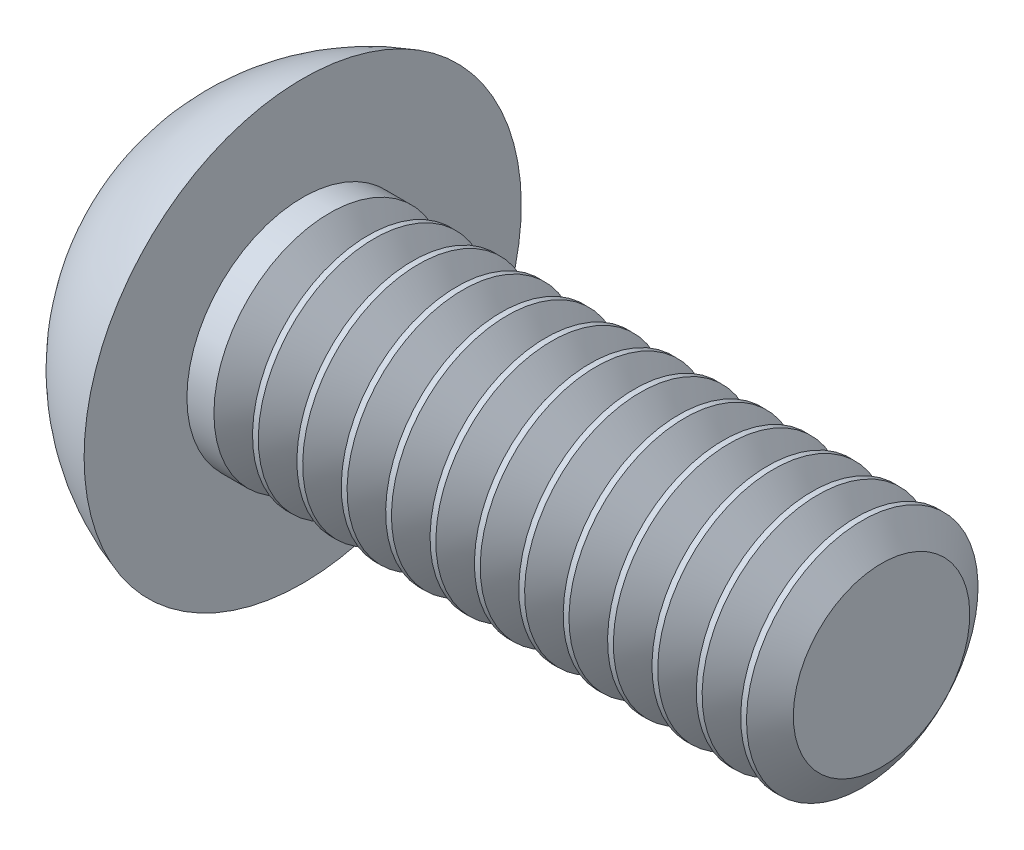
SolidWorks part; units mm, degrees
ref_plane "Plane1" through (0, 0, 0) normal (0, 0, 1) x (1, 0, 0)
ref_plane "Plane2" through (0, 0, 0) normal (0, 1, 0) x (1, 0, 0)
ref_plane "Plane3" through (0, 0, 0) normal (1, 0, 0) x (0, 0, -1)
sketch "BodySke" plane through (0, 0, 0) normal (0, 0, 1) x (1, 0, 0)
  line L0 (0, 0) -> (82.55, 0) construction
  line L1 (20.32, 0) -> (20.32, 3.175)
  line L2 (20.32, 3.175) -> (4.445, 3.175)
  line L3 (4.445, 3.175) -> (4.445, 5.9944)
  line L4 (20.32, -3.175) -> (4.445, -3.175) construction
  line L5 (4.445, -3.175) -> (4.445, -5.9944) construction
  line L6 (5.715, 12.7) -> (5.715, -3.175) construction
  line L7 (20.32, 0) -> (0, 0)
  line L8 (4.445, 12.7) -> (4.445, -3.175) construction
  arc A0 (0, 0) -> (4.445, 5.9944) centre (6.2644, 0) cw
  dimension "Head_ht" = 4.445
  dimension "Diameter" = 6.35
  dimension "Head_dia" = 11.9888
  dimension "Length" = 15.875
  dimension "Thread_nom" = 15.875
  dimension "Advance" = 1.27
revolve "Base-Revolve" add sketch "BodySke"
cosmetic thread "ThreadCosmetic" [suppressed]
revolve "ThreadSchematic" cut sketch "ThdSchSke" angle 360 about L3
sketch "ThdSchSke" plane through (0, 0, 0) normal (0, 0, 1) x (1, 0, 0)
  line L0 (5.715, -2.4193) -> (5.1859, -3.175)
  line L1 (5.715, -2.4193) -> (6.2441, -3.175)
  line L2 (6.2441, -3.175) -> (6.2441, -3.9688)
  line L3 (-3.175, 0) -> (5.1513, 0) construction
  line L5 (6.2441, -3.9688) -> (5.1859, -3.9688)
  line L6 (5.1859, -3.9688) -> (5.1859, -3.175)
  dimension "Diameter" = 6.35
  dimension "SideAngle" = 55
  dimension "VeeAngle" = 70
  dimension "Thread_minor" = 4.8387
  dimension "Overcut" = 7.9375
  dimension "Start" = 5.715
sketch "Sketch2" plane through (0, 0, 0) normal (1, 0, 0) x (0, 0, -1)
  line L0 (5.9944, 0.9525) -> (-5.9944, 0.9525)
  line L1 (5.9944, 0.9525) -> (5.9944, -0.9525)
  line L2 (-5.9944, -0.9525) -> (5.9944, -0.9525)
  line L3 (-5.9944, -0.9525) -> (-5.9944, 0.9525)
  dimension "D1" = 11.9888
  dimension "Slot_width" = 1.905
  dimension "D2" = 5.9944
  dimension "D3" = 0.9525
extrude "Slot" [suppressed] cut sketch "Sketch2" along normal blind 2.7686
sketch "Sketch3" plane through (0, 0, 0) normal (1, 0, 0) x (0, 0, -1)
  line L0 (0.6858, -3.8989) -> (-0.6858, -3.8989)
  line L1 (0.6858, -3.8989) -> (0.6858, 3.8989)
  line L2 (-0.6858, 3.8989) -> (0.6858, 3.8989)
  line L3 (-0.6858, 3.8989) -> (-0.6858, -3.8989)
  dimension "Cross_width" = 1.3716
  dimension "D1" = 0.6858
  dimension "Cross_dia" = 7.7978
  dimension "D2" = 3.8989
ref_plane "Plane4" through (4.5974, 0, 0) normal (1, 0, 0) x (0, 0, -1)
sketch "Sketch4" plane through (4.5974, 0, 0) normal (1, 0, 0) x (0, 0, -1)
  line L0 (0.3429, -0.3429) -> (-0.3429, -0.3429)
  line L1 (0.3429, -0.3429) -> (0.3429, 0.3429)
  line L2 (-0.3429, 0.3429) -> (0.3429, 0.3429)
  line L3 (-0.3429, 0.3429) -> (-0.3429, -0.3429)
  dimension "D1" = 0.6858
  dimension "D2" = 0.3429
  dimension "D3" = 0.6858
  dimension "D4" = 0.3429
loft "Cross" cut profiles "Sketch3", "Sketch4"
pattern_circular "CirPattern1" count 2 every 90 about axis through (0, 0, 0) along (1, 0, 0) of "Cross"
pattern_linear "ThdSchPat" count 13 spacing 1.2171 along (1, 0, 0) of "ThreadSchematic"
equation "\"D1@Sketch2\" = \"Head_dia@BodySke\""
equation "\"D2@Sketch2\" = \"D1@Sketch2\" / 2"
equation "\"D3@Sketch2\" = \"Slot_width@Sketch2\" / 2"
equation "\"D1@Sketch3\" = \"Cross_width@Sketch3\" / 2"
equation "\"D2@Sketch3\" = \"Cross_dia@Sketch3\" / 2"
equation "\"D1@Sketch4\" = \"Cross_width@Sketch3\" *.5"
equation "\"D2@Sketch4\" = \"D1@Sketch4\" / 2"
equation "\"D3@Sketch4\" = \"D1@Sketch4\""
equation "\"D4@Sketch4\" = \"D2@Sketch4\""
equation "\"Thread_length@ThreadCosmetic\" = ((sgn( (\"Length@BodySke\" - \"Advance@BodySke\" ) - \"Thread_nom@BodySke\" )-1)*( (\"Length@BodySke\" - \"Advance@BodySke\" ) - \"Thread_nom@BodySke\" ))/-2+ \"Thread_nom@BodySke\""
equation "\"Thread_minor@ThdSchSke\" = \"Thread_minor@ThreadCosmetic\""
equation "\"Diameter@ThdSchSke\" = \"Diameter@BodySke\""
equation "\"Overcut@ThdSchSke\" = \"Diameter@BodySke\" * 1.25"
equation "\"Start@ThdSchSke\" = \"Head_ht@BodySke\" + \"Length@BodySke\" - \"Thread_length@ThreadCosmetic\"  '---Non-countersunk---"
equation "\"Num_threads@ThdSchPat\" = int( \"Thread_length@ThreadCosmetic\" / \"Advance@BodySke\" + 0.999 )  + 1"
equation "\"Advance@ThdSchPat\" = \"Thread_length@ThreadCosmetic\" /  (\"Num_threads@ThdSchPat\" - 1) 'relax it"
